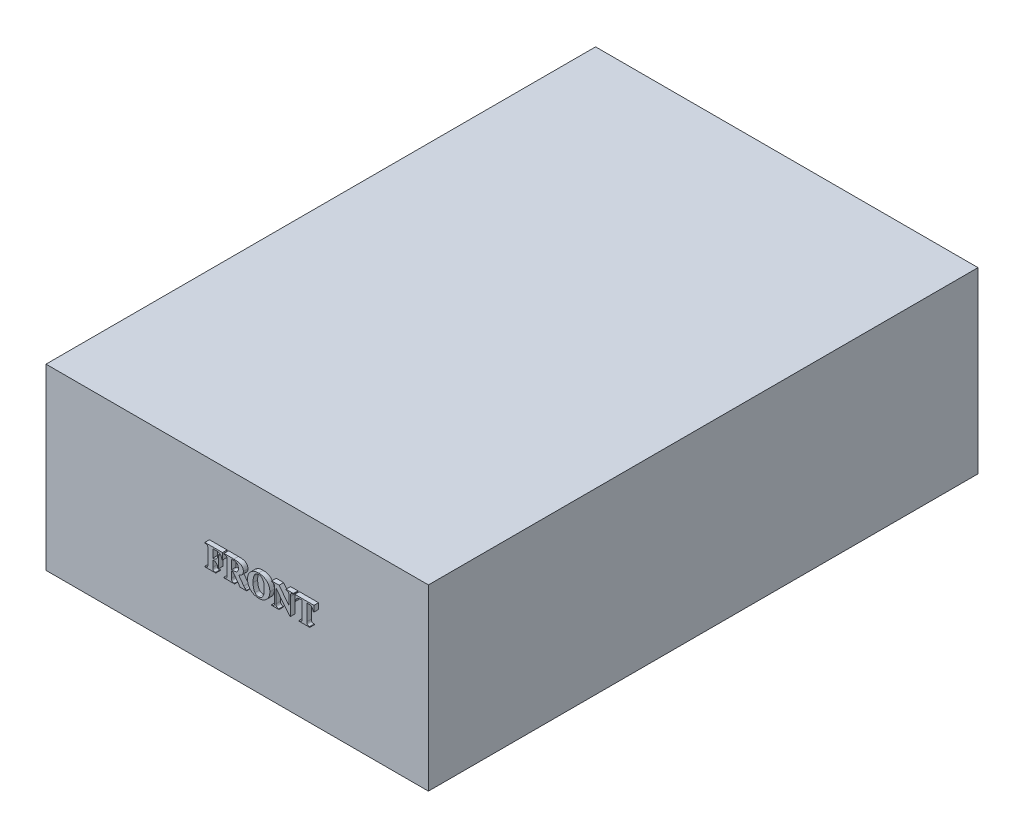
SolidWorks part; units mm, degrees
ref_plane "Front Plane" through (0, 0, 0) normal (0, 0, 1) x (1, 0, 0)
ref_plane "Top Plane" through (0, 0, 0) normal (0, 1, 0) x (1, 0, 0)
ref_plane "Right Plane" through (0, 0, 0) normal (1, 0, 0) x (0, 0, -1)
sketch "Sketch1" plane through (0, 0, 0) normal (0, 0, 1) x (1, 0, 0)
  line L1 (-106.045, 99.06) -> (106.045, 99.06)
  line L2 (-106.045, 99.06) -> (-106.045, 0)
  line L3 (-106.045, 0) -> (106.045, 0)
  line L4 (106.045, 99.06) -> (106.045, 0)
  point P4 (0, 0)
  dimension "D1" = 212.09
  dimension "D2" = 99.06
extrude "Extrude1" add sketch "Sketch1" against normal blind 304.8
sketch "Sketch2" plane through (0, 0, 0) normal (0, 0, 1) x (1, 0, 0)
  text T0 "<b>FRONT</b>" font "Times New Roman" height in points 48
extrude "Extrude2" add sketch "Sketch2" along normal blind 2.54 separate body
